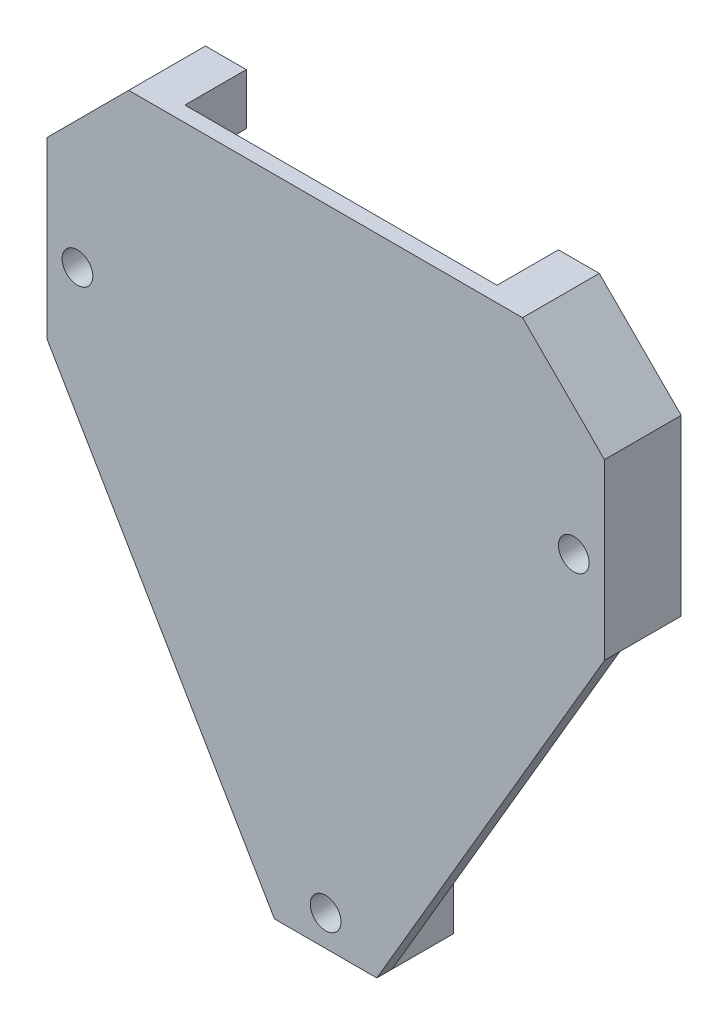
SolidWorks part; units mm, degrees
ref_plane "Спереди" through (0, 0, 0) normal (0, 0, 1) x (1, 0, 0)
ref_plane "Сверху" through (0, 0, 0) normal (0, 1, 0) x (1, 0, 0)
ref_plane "Справа" through (0, 0, 0) normal (1, 0, 0) x (0, 0, -1)
sketch "Эскиз1" plane through (0, 0, 0) normal (0, 0, 1) x (1, 0, 0)
  line L0 (55, 289.53) -> (55, 50289.53) construction
  line L1 (39.75, 326) -> (39.75, 321)
  line L2 (-109, 326) -> (109, 326) construction
  line L3 (39.75, 321) -> (35, 321)
  line L4 (35, 321) -> (35, 301)
  line L5 (82.25, 301) -> (75, 301)
  line L6 (39.75, 326) -> (35.7574, 326)
  line L7 (35.7574, 326) -> (27.75, 317.9926)
  line L8 (27.75, 317.9926) -> (27.75, 301)
  line L9 (27.75, 301) -> (35, 301)
  line L10 (82.25, 317.9926) -> (82.25, 301)
  line L11 (74.2426, 326) -> (82.25, 317.9926)
  line L12 (70.25, 326) -> (74.2426, 326)
  line L13 (75, 321) -> (75, 301)
  line L14 (70.25, 321) -> (75, 321)
  line L15 (70.25, 326) -> (70.25, 321)
  line L16 (50, 270) -> (50, 263)
  line L17 (50, 263) -> (60, 263)
  line L18 (50, 270) -> (60, 270)
  line L19 (60, 270) -> (60, 263)
  circle A0 centre (79.25, 308.5) radius 1.5 construction
  circle A1 centre (55, 266) radius 1.5 construction
  circle A2 centre (30.75, 308.5) radius 1.5 construction
  circle A3 centre (79.25, 308.5) radius 1.5
  circle A4 centre (55, 266) radius 1.5
  circle A5 centre (30.75, 308.5) radius 1.5
  dimension "D1" = 30.5
  dimension "D2" = 5
  dimension "D3" = 20
  dimension "D4" = 40
  dimension "D5" = 3
  dimension "D6" = 45
  dimension "D7" = 3
  dimension "D8" = 3
  dimension "D9" = 4
  dimension "D10" = 10
extrude "Бобышка-Вытянуть1" add sketch "Эскиз1" along normal blind 6
sketch "Эскиз2" plane through (0, 0, 6) normal (0, 0, 1) x (1, 0, 0)
  line L0 (82.25, 301) -> (82.25, 317.9926) construction
  line L1 (82.25, 317.9926) -> (74.2426, 326) construction
  line L2 (74.2426, 326) -> (70.25, 326) construction
  line L3 (50, 263) -> (60, 263) construction
  line L4 (27.75, 317.9926) -> (27.75, 301) construction
  line L5 (35.7574, 326) -> (27.75, 317.9926) construction
  line L6 (39.75, 326) -> (35.7574, 326) construction
  line L7 (82.25, 301) -> (82.25, 317.9926)
  line L8 (82.25, 317.9926) -> (74.2426, 326)
  line L9 (74.2426, 326) -> (70.25, 326)
  line L10 (50, 263) -> (60, 263)
  line L11 (27.75, 317.9926) -> (27.75, 301)
  line L12 (35.7574, 326) -> (27.75, 317.9926)
  line L13 (39.75, 326) -> (35.7574, 326)
  line L14 (39.75, 326) -> (70.25, 326)
  line L15 (27.75, 301) -> (50, 263)
  line L16 (60, 263) -> (82.25, 301)
  circle A0 centre (55, 266) radius 1.5 construction
  circle A1 centre (79.25, 308.5) radius 1.5 construction
  circle A2 centre (30.75, 308.5) radius 1.5 construction
  circle A3 centre (55, 266) radius 1.5
  circle A4 centre (79.25, 308.5) radius 1.5
  circle A5 centre (30.75, 308.5) radius 1.5
extrude "Бобышка-Вытянуть2" add sketch "Эскиз2" along normal blind 1.5
sketch "Эскиз3" plane through (0, 270, 0) normal (0, 1, 0) x (1, 0, 0)
  line L0 (60, 0) -> (50, 0) construction
  line L1 (70.25, -6) -> (39.75, -6) construction
  circle A0 centre (55, -3.5) radius 1
  point P5 (55, 0)
  dimension "D1" = 2
  dimension "D2" = 2.5
extrude "Бобышка-Вытянуть3" add sketch "Эскиз3" along normal blind 1.5
